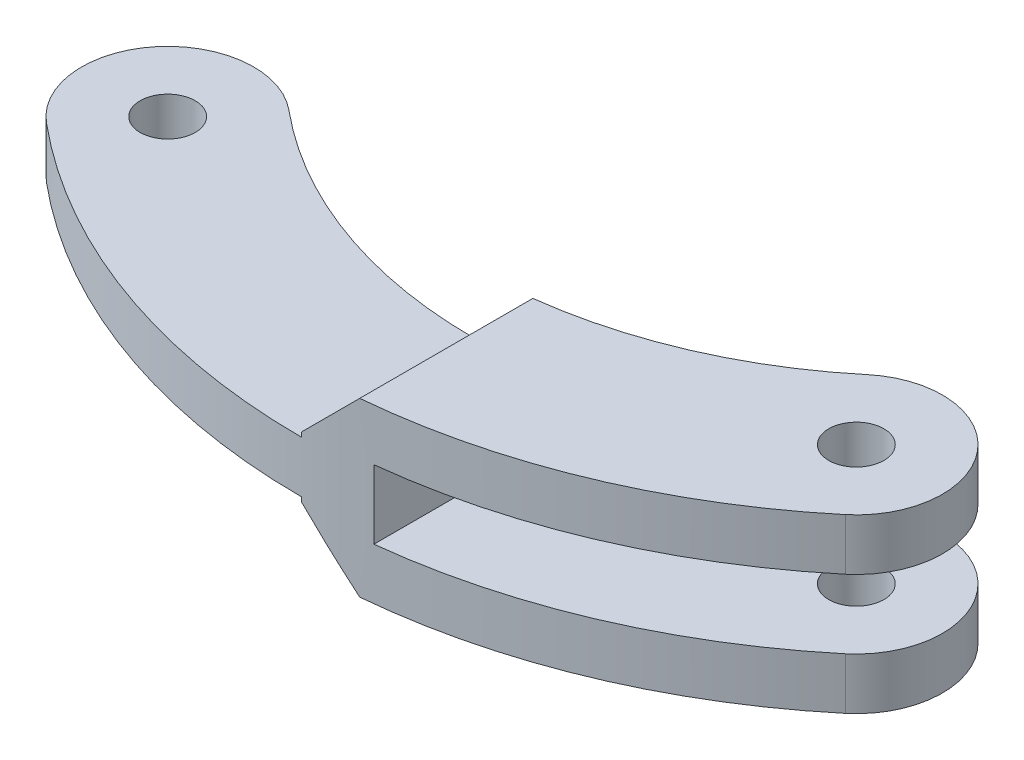
SolidWorks part; units mm, degrees
ref_plane "Front" through (0, 0, 0) normal (0, 0, 1) x (1, 0, 0)
ref_plane "Top" through (0, 0, 0) normal (0, 1, 0) x (1, 0, 0)
ref_plane "Right" through (0, 0, 0) normal (1, 0, 0) x (0, 0, -1)
sketch "Sketch1" plane through (0, 0, 0) normal (0, 1, 0) x (1, 0, 0)
  circle A0 centre (0, 0) radius 0.8
  circle A1 centre (20, 0) radius 0.8
  arc A2 (1.6005, 1.9206) -> (-1.6005, -1.9206) centre (0, 0) ccw
  arc A3 (18.3995, 1.9206) -> (21.6005, -1.9206) centre (20, 0) cw
  arc A4 (-1.6005, -1.9206) -> (21.6005, -1.9206) centre (10, 12) ccw
  arc A5 (18.3995, 1.9206) -> (1.6005, 1.9206) centre (10, 12) cw
  point P13 (-1.9206, 1.6005)
  point P14 (21.9206, 1.6005)
  dimension "D1" = 1.6
  dimension "D2" = 1.6
  dimension "D4" = 2.5
  dimension "D3" = 20
  dimension "D5" = 12
extrude "Boss-Extrude1" add sketch "Sketch1" along normal mid plane 1.5
sketch "Sketch2" plane through (0, 0, 0) normal (0, 1, 0) x (1, 0, 0)
  line L5 (10, -1.1205) -> (10, -6.1205)
  arc A0 (18.3995, 1.9206) -> (21.6005, -1.9206) centre (20, 0) cw
  circle A1 centre (20, 0) radius 0.8
  circle A2 centre (0, 0) radius 0.8 construction
  circle A3 centre (20, 0) radius 0.8 construction
  arc A4 (1.6005, 1.9206) -> (18.3995, 1.9206) centre (10, 12) ccw construction
  arc A5 (-1.6005, -1.9206) -> (21.6005, -1.9206) centre (10, 12) ccw construction
  arc A6 (10, -1.1205) -> (18.3995, 1.9206) centre (10, 12) ccw
  arc A7 (10, -6.1205) -> (21.6005, -1.9206) centre (10, 12) ccw
extrude "Boss-Extrude2" add sketch "Sketch2" along normal mid plane 5
chamfer "Chamfer1" distance 1.625 angle 45 2 edges at (10, 2.5, 3.6205) (10, -2.5, 3.6205)
sketch "Sketch3" plane through (0, 0, 0) normal (0, 0, -1) x (-1, 0, 0)
  line L0 (-22.5, 2.5) -> (-22.5, -2.5) construction
  line L1 (-22.5, -1) -> (-12, -1)
  line L2 (-22.5, -1) -> (-22.5, 1)
  line L3 (-22.5, 1) -> (-12, 1)
  line L4 (-12, -1) -> (-12, 1)
  line L5 (-10, -0.75) -> (-10, -0.875) construction
  point P6 (-12, 0)
  dimension "D1" = 2
  dimension "D2" = 2
extrude "Cut-Extrude1" cut sketch "Sketch3" against normal through all both and the other way through all
